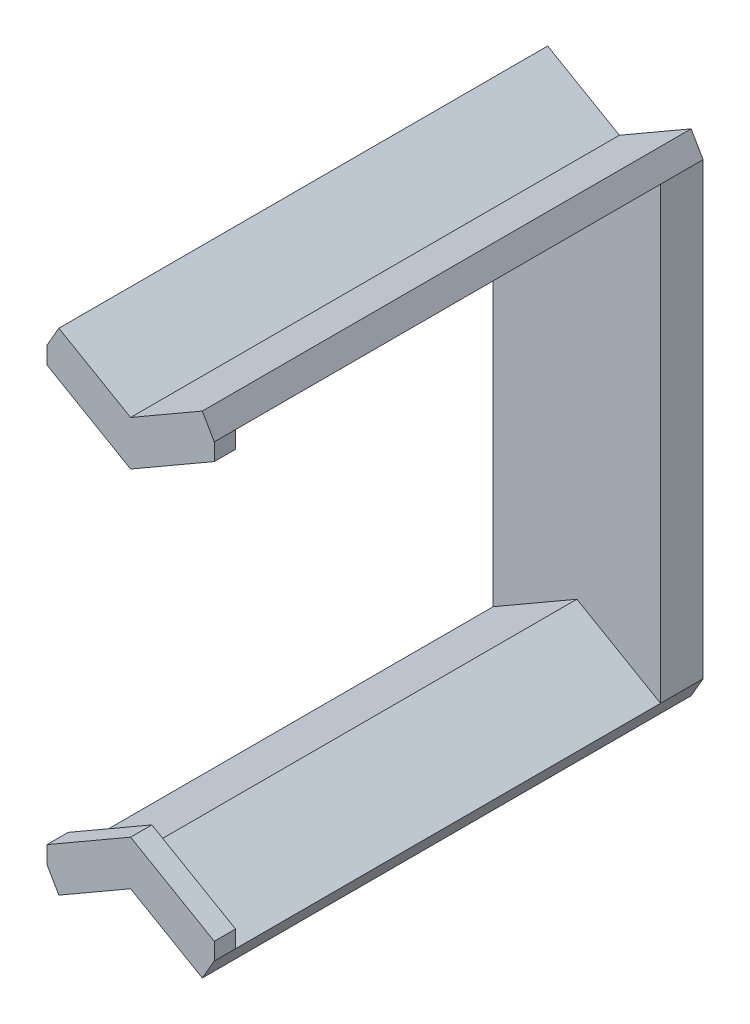
SolidWorks part; units mm, degrees
ref_plane "Front Plane" through (0, 0, 0) normal (0, 0, 1) x (1, 0, 0)
ref_plane "Top Plane" through (0, 0, 0) normal (0, 1, 0) x (1, 0, 0)
ref_plane "Right Plane" through (0, 0, 0) normal (1, 0, 0) x (0, 0, -1)
sketch "Sketch1" plane through (0, 0, 0) normal (0, 0, 1) x (1, 0, 0)
  line L0 (0, -3.75) -> (0, 3.75)
  line L1 (0, 3.75) -> (0, 6.75)
  line L2 (0, -3.75) -> (0, -6.75)
  line L3 (2.8579, 0) -> (-2.8579, 0) construction
  line L4 (0, 3.75) -> (2.5981, 5.25)
  line L5 (2.5981, 5.25) -> (2.5981, 8.25)
  line L6 (2.5981, 8.25) -> (0, 9.75)
  line L7 (0, 9.75) -> (-2.5981, 8.25)
  line L8 (-2.5981, 8.25) -> (-2.5981, 5.25)
  line L9 (-2.5981, 5.25) -> (0, 3.75)
  line L10 (0, -3.75) -> (-2.5981, -5.25)
  line L11 (-2.5981, -5.25) -> (-2.5981, -8.25)
  line L12 (-2.5981, -8.25) -> (0, -9.75)
  line L13 (0, -9.75) -> (2.5981, -8.25)
  line L14 (2.5981, -8.25) -> (2.5981, -5.25)
  line L15 (2.5981, -5.25) -> (0, -3.75)
  line L16 (0, 4.1519) -> (2.25, 5.451)
  line L17 (2.25, 5.451) -> (2.25, 8.049)
  line L18 (2.25, 8.049) -> (0, 9.3481)
  line L19 (0, 9.3481) -> (-2.25, 8.049)
  line L20 (-2.25, 8.049) -> (-2.25, 5.451)
  line L21 (-2.25, 5.451) -> (0, 4.1519)
  line L22 (0, 4.8014) -> (1.6875, 5.7757)
  line L23 (1.6875, 5.7757) -> (1.6875, 7.7243)
  line L24 (1.6875, 7.7243) -> (0, 8.6986)
  line L25 (0, 8.6986) -> (-1.6875, 7.7243)
  line L26 (-1.6875, 7.7243) -> (-1.6875, 5.7757)
  line L27 (-1.6875, 5.7757) -> (0, 4.8014)
  line L28 (-1.6875, -5.7757) -> (0, -4.8014)
  line L29 (-1.6875, -7.7243) -> (-1.6875, -5.7757)
  line L30 (0, -8.6986) -> (-1.6875, -7.7243)
  line L31 (1.6875, -7.7243) -> (0, -8.6986)
  line L32 (1.6875, -5.7757) -> (1.6875, -7.7243)
  line L33 (0, -4.8014) -> (1.6875, -5.7757)
  line L34 (-2.25, -5.451) -> (0, -4.1519)
  line L35 (-2.25, -8.049) -> (-2.25, -5.451)
  line L36 (0, -9.3481) -> (-2.25, -8.049)
  line L37 (2.25, -8.049) -> (0, -9.3481)
  line L38 (2.25, -5.451) -> (2.25, -8.049)
  line L39 (0, -4.1519) -> (2.25, -5.451)
  line L40 (-1.9688, -5.2886) -> (-1.6875, -5.7757)
  line L41 (-1.9688, 5.2886) -> (-1.9688, -5.2886)
  line L42 (1.6875, 5.7757) -> (1.9688, 5.2886)
  line L43 (1.9688, 5.2886) -> (1.9688, -5.2886)
  line L44 (1.9688, -5.2886) -> (1.6875, -5.7757)
  line L45 (-1.6875, 5.7757) -> (-1.9688, 5.2886)
  circle A0 centre (0, 6.75) radius 2.5981 construction
  circle A1 centre (0, -6.75) radius 2.5981 construction
  circle A2 centre (0, 6.75) radius 2.25 construction
  circle A4 centre (0, -6.75) radius 1.6875 construction
  circle A5 centre (0, -6.75) radius 2.25 construction
  circle A6 centre (0, -6.75) radius 2.5981 construction
  point P4 (0, 0)
  dimension "D1" = 7.5
extrude "Boss-Extrude1" add sketch "Sketch1" along normal blind 1 contours L34 L40 L28 L2 | L44 L39 L2 L33 | L43 L4 L0 L15 | L9 L41 L10 L0 | L43 L15 L2 L39 | L10 L41 L34 L2 | L21 L41 L9 L1 | L27 L45 L21 L1 | L42 L22 L1 L16 | L43 L16 L1 L4
sketch "Sketch2" plane through (0, 0, 0) normal (0, 0, 1) x (1, 0, 0)
  line L0 (0, -3.75) -> (0, 3.75)
  line L1 (0, 3.75) -> (0, 6.75)
  line L2 (0, -3.75) -> (0, -6.75)
  line L4 (0, 3.75) -> (2.5981, 5.25)
  line L5 (2.5981, 5.25) -> (2.5981, 8.25)
  line L6 (2.5981, 8.25) -> (0, 9.75)
  line L7 (0, 9.75) -> (-2.5981, 8.25)
  line L8 (-2.5981, 8.25) -> (-2.5981, 5.25)
  line L9 (-2.5981, 5.25) -> (0, 3.75)
  line L10 (0, -3.75) -> (-2.5981, -5.25)
  line L11 (-2.5981, -5.25) -> (-2.5981, -8.25)
  line L12 (-2.5981, -8.25) -> (0, -9.75)
  line L13 (0, -9.75) -> (2.5981, -8.25)
  line L14 (2.5981, -8.25) -> (2.5981, -5.25)
  line L15 (2.5981, -5.25) -> (0, -3.75)
  line L16 (0, 4.1519) -> (2.25, 5.451)
  line L17 (2.25, 5.451) -> (2.25, 8.049)
  line L18 (2.25, 8.049) -> (0, 9.3481)
  line L19 (0, 9.3481) -> (-2.25, 8.049)
  line L20 (-2.25, 8.049) -> (-2.25, 5.451)
  line L21 (-2.25, 5.451) -> (0, 4.1519)
  line L22 (0, 4.8014) -> (1.6875, 5.7757)
  line L23 (1.6875, 5.7757) -> (1.6875, 7.7243)
  line L24 (1.6875, 7.7243) -> (0, 8.6986)
  line L25 (0, 8.6986) -> (-1.6875, 7.7243)
  line L26 (-1.6875, 7.7243) -> (-1.6875, 5.7757)
  line L27 (-1.6875, 5.7757) -> (0, 4.8014)
  line L28 (-1.6875, -5.7757) -> (0, -4.8014)
  line L29 (-1.6875, -7.7243) -> (-1.6875, -5.7757)
  line L30 (0, -8.6986) -> (-1.6875, -7.7243)
  line L31 (1.6875, -7.7243) -> (0, -8.6986)
  line L32 (1.6875, -5.7757) -> (1.6875, -7.7243)
  line L33 (0, -4.8014) -> (1.6875, -5.7757)
  line L34 (-2.25, -5.451) -> (0, -4.1519)
  line L35 (-2.25, -8.049) -> (-2.25, -5.451)
  line L36 (0, -9.3481) -> (-2.25, -8.049)
  line L37 (2.25, -8.049) -> (0, -9.3481)
  line L38 (2.25, -5.451) -> (2.25, -8.049)
  line L39 (0, -4.1519) -> (2.25, -5.451)
  line L40 (-1.9688, -5.2886) -> (-1.6875, -5.7757)
  line L41 (-1.9688, 5.2886) -> (-1.9688, -5.2886)
  line L42 (1.6875, 5.7757) -> (1.9688, 5.2886)
  line L43 (1.9688, 5.2886) -> (1.9688, -5.2886)
  line L44 (1.9688, -5.2886) -> (1.6875, -5.7757)
  line L45 (-1.6875, 5.7757) -> (-1.9688, 5.2886)
  circle A0 centre (0, 6.75) radius 2.5981 construction
  circle A1 centre (0, -6.75) radius 2.5981 construction
  circle A2 centre (0, 6.75) radius 2.25 construction
  circle A4 centre (0, -6.75) radius 1.6875 construction
  circle A5 centre (0, -6.75) radius 2.25 construction
  circle A6 centre (0, -6.75) radius 2.5981 construction
  point P4 (0, 0)
  dimension "D1" = 7.5
extrude "Boss-Extrude2" add sketch "Sketch2" along normal blind 11 contours L34 L40 L28 L2 | L44 L39 L2 L33 | L27 L45 L21 L1 | L42 L22 L1 L16
ref_plane "Plane1" through (0, 0, 11) normal (0, 0, 1) x (1, 0, 0)
sketch "Sketch5" plane through (0, 0, 11) normal (0, 0, 1) x (1, 0, 0)
  line L0 (0, -3.75) -> (0, 3.75)
  line L1 (0, 3.75) -> (0, 6.75)
  line L2 (0, -3.75) -> (0, -6.75)
  line L4 (0, 3.75) -> (2.5981, 5.25)
  line L5 (2.5981, 5.25) -> (2.5981, 8.25)
  line L6 (2.5981, 8.25) -> (0, 9.75)
  line L7 (0, 9.75) -> (-2.5981, 8.25)
  line L8 (-2.5981, 8.25) -> (-2.5981, 5.25)
  line L9 (-2.5981, 5.25) -> (0, 3.75)
  line L10 (0, -3.75) -> (-2.5981, -5.25)
  line L11 (-2.5981, -5.25) -> (-2.5981, -8.25)
  line L12 (-2.5981, -8.25) -> (0, -9.75)
  line L13 (0, -9.75) -> (2.5981, -8.25)
  line L14 (2.5981, -8.25) -> (2.5981, -5.25)
  line L15 (2.5981, -5.25) -> (0, -3.75)
  line L16 (0, 4.1519) -> (2.25, 5.451)
  line L17 (2.25, 5.451) -> (2.25, 8.049)
  line L18 (2.25, 8.049) -> (0, 9.3481)
  line L19 (0, 9.3481) -> (-2.25, 8.049)
  line L20 (-2.25, 8.049) -> (-2.25, 5.451)
  line L21 (-2.25, 5.451) -> (0, 4.1519)
  line L22 (0, 4.8014) -> (1.6875, 5.7757)
  line L23 (1.6875, 5.7757) -> (1.6875, 7.7243)
  line L24 (1.6875, 7.7243) -> (0, 8.6986)
  line L25 (0, 8.6986) -> (-1.6875, 7.7243)
  line L26 (-1.6875, 7.7243) -> (-1.6875, 5.7757)
  line L27 (-1.6875, 5.7757) -> (0, 4.8014)
  line L28 (-1.6875, -5.7757) -> (0, -4.8014)
  line L29 (-1.6875, -7.7243) -> (-1.6875, -5.7757)
  line L30 (0, -8.6986) -> (-1.6875, -7.7243)
  line L31 (1.6875, -7.7243) -> (0, -8.6986)
  line L32 (1.6875, -5.7757) -> (1.6875, -7.7243)
  line L33 (0, -4.8014) -> (1.6875, -5.7757)
  line L34 (-2.25, -5.451) -> (0, -4.1519)
  line L35 (-2.25, -8.049) -> (-2.25, -5.451)
  line L36 (0, -9.3481) -> (-2.25, -8.049)
  line L37 (2.25, -8.049) -> (0, -9.3481)
  line L38 (2.25, -5.451) -> (2.25, -8.049)
  line L39 (0, -4.1519) -> (2.25, -5.451)
  line L40 (-1.9688, -5.2886) -> (-1.6875, -5.7757)
  line L41 (-1.9688, 5.2886) -> (-1.9688, -5.2886)
  line L42 (1.6875, 5.7757) -> (1.9688, 5.2886)
  line L43 (1.9688, 5.2886) -> (1.9688, -5.2886)
  line L44 (1.9688, -5.2886) -> (1.6875, -5.7757)
  line L45 (-1.6875, 5.7757) -> (-1.9688, 5.2886)
  circle A0 centre (0, 6.75) radius 2.5981 construction
  circle A1 centre (0, -6.75) radius 2.5981 construction
  circle A2 centre (0, 6.75) radius 2.25 construction
  circle A4 centre (0, -6.75) radius 1.6875 construction
  circle A5 centre (0, -6.75) radius 2.25 construction
  circle A6 centre (0, -6.75) radius 2.5981 construction
  point P4 (0, 0)
  dimension "D1" = 7.5
extrude "Boss-Extrude4" add sketch "Sketch5" along normal blind 0.5 contours L43 L15 L2 L39 | L44 L39 L2 L33 | L34 L40 L28 L2 | L10 L41 L34 L2 | L42 L22 L1 L16 | L43 L16 L1 L4 | L27 L45 L21 L1 | L21 L41 L9 L1
